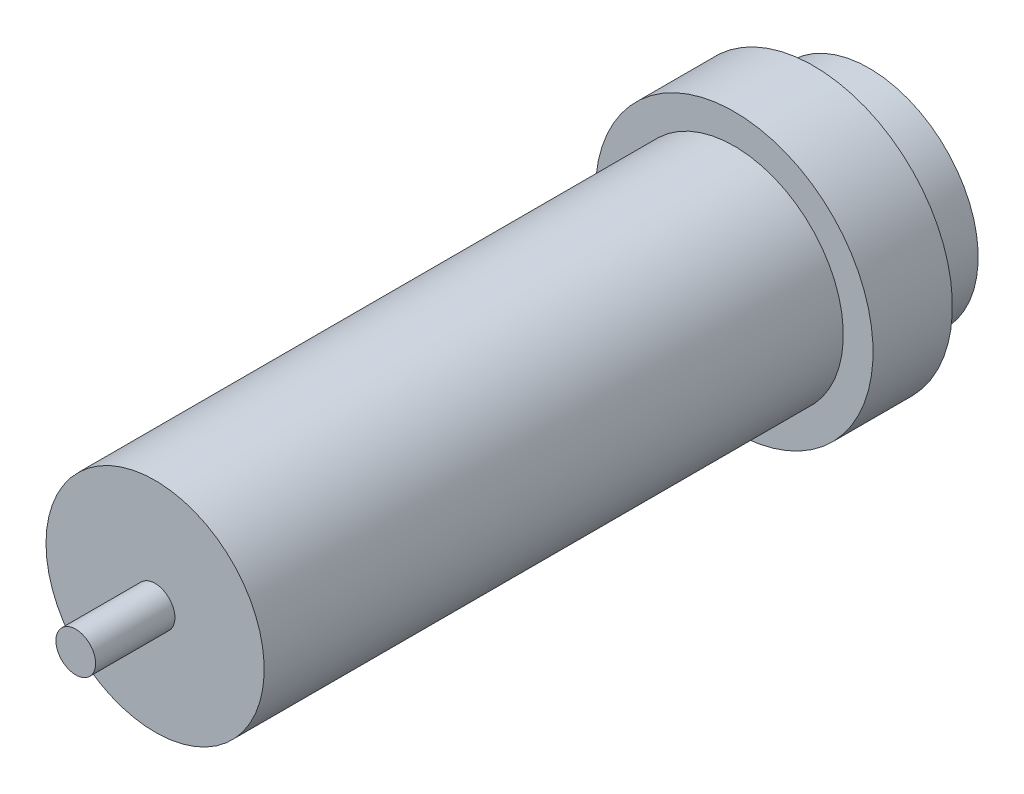
SolidWorks part; units mm, degrees
ref_plane "Front Plane" through (0, 0, 0) normal (0, 0, 1) x (1, 0, 0)
ref_plane "Top Plane" through (0, 0, 0) normal (0, 1, 0) x (1, 0, 0)
ref_plane "Right Plane" through (0, 0, 0) normal (1, 0, 0) x (0, 0, -1)
sketch "Sketch1" plane through (0, 0, 0) normal (0, 0, 1) x (1, 0, 0)
  circle A0 centre (0, 0) radius 1.25
  dimension "D1" = 2.5
extrude "Boss-Extrude1" add sketch "Sketch1" along normal blind 2.5 contours A0
sketch "Sketch2" plane through (0, 0, 2.5) normal (0, 0, 1) x (1, 0, 0)
  circle A0 centre (0, 0) radius 6.875
  dimension "D1" = 13.75
extrude "Boss-Extrude2" add sketch "Sketch2" along normal blind 45
ref_plane "Plane1" through (0, 0, 8.5) normal (0, 0, -1) x (-1, 0, 0)
sketch "Sketch3" plane through (0, 0, 8.5) normal (0, 0, -1) x (-1, 0, 0)
  circle A0 centre (0, 0) radius 8.75
  dimension "D1" = 17.5
extrude "Boss-Extrude3" add sketch "Sketch3" along normal blind 2.5 and the other way blind 2.5
sketch "Sketch5" plane through (0, 0, 47.5) normal (0, 0, 1) x (1, 0, 0)
  circle A0 centre (0, 0) radius 1.25
  dimension "D1" = 2.5
extrude "Boss-Extrude4" add sketch "Sketch5" along normal blind 5
ref_plane "Plane2" through (0, 0, 44) normal (0, 0, 1) x (1, 0, 0)
sketch "Sketch7" plane through (0, 0, 44) normal (0, 0, 1) x (1, 0, 0)
  line L0 (-8.75, 0) -> (8.75, 0)
  circle A0 centre (0, 0) radius 8.75 construction
